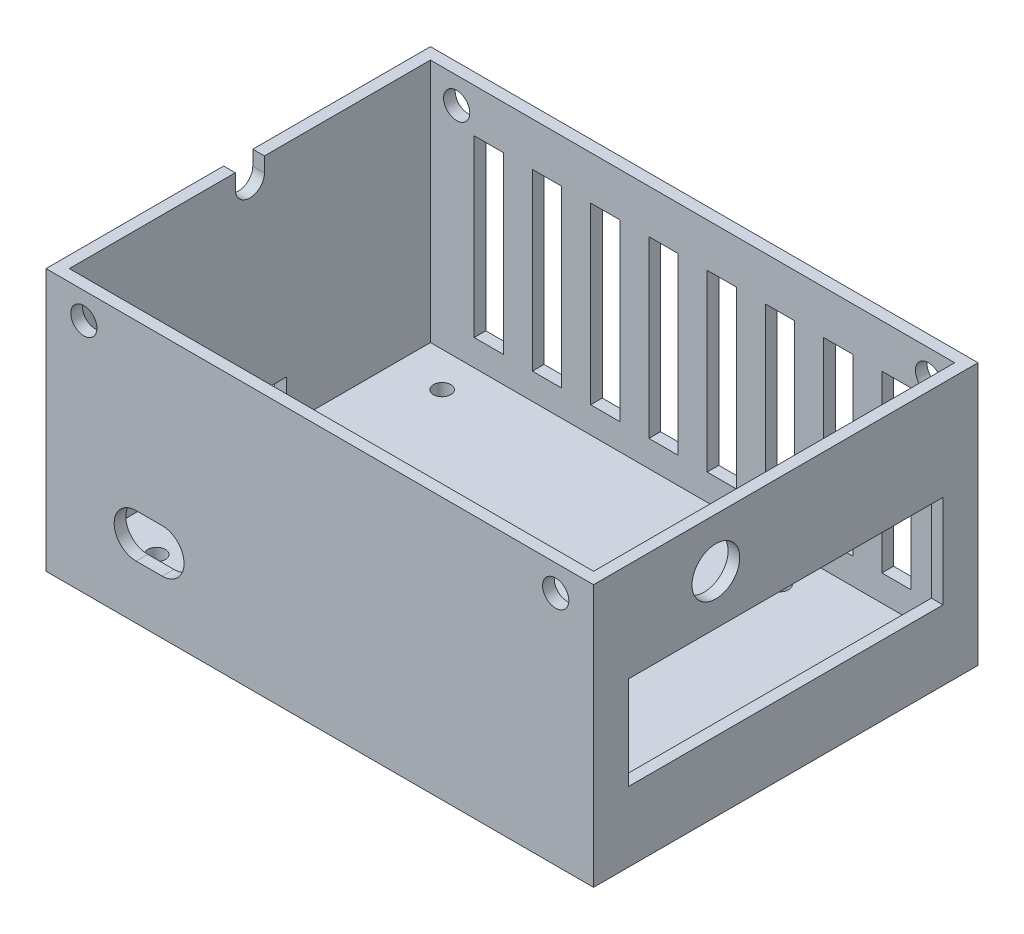
SolidWorks part; units mm, degrees
ref_plane "Front Plane" through (0, 0, 0) normal (0, 0, 1) x (1, 0, 0)
ref_plane "Top Plane" through (0, 0, 0) normal (0, 1, 0) x (1, 0, 0)
ref_plane "Right Plane" through (0, 0, 0) normal (1, 0, 0) x (0, 0, -1)
sketch "Sketch1" plane through (0, 0, 0) normal (0, 1, 0) x (1, 0, 0)
  line L1 (-45, -31) -> (45, -31)
  line L2 (-45, -31) -> (-45, 31)
  line L3 (-45, 31) -> (45, 31)
  line L4 (45, -31) -> (45, 31)
  line L5 (-45, -31) -> (45, 31) construction
  line L6 (-45, 31) -> (45, -31) construction
  point P0 (0, 0)
  dimension "D1" = 90
  dimension "D2" = 62
extrude "Boss-Extrude1" add sketch "Sketch1" along normal blind 3
sketch "Sketch2" plane through (0, 3, 0) normal (0, 1, 0) x (1, 0, 0)
  line L0 (-45, -31) -> (45, -31) construction
  line L1 (-45, 31) -> (-45, -31) construction
  circle A0 centre (-37, -24) radius 1.5
  circle A1 centre (21, -24) radius 1.5
  circle A2 centre (21, 25) radius 1.5
  circle A3 centre (-37, 25) radius 1.5
  dimension "D1" = 3
  dimension "D2" = 7
  dimension "D3" = 8
  dimension "D5" = 58
  dimension "D6" = 2
  dimension "D7" = 49
  dimension "D4" = 2
extrude "Cut-Extrude1" cut sketch "Sketch2" against normal up to next
sketch "Sketch3" plane through (0, 0, 0) normal (0, 1, 0) x (1, 0, 0)
  line L1 (-45, -31) -> (45, -31)
  line L2 (-45, -31) -> (-45, 31)
  line L3 (-45, 31) -> (45, 31)
  line L4 (45, -31) -> (45, 31)
  line L5 (-45, -31) -> (45, 31) construction
  line L6 (-45, 31) -> (45, -31) construction
  line L7 (-47, -33) -> (47, -33)
  line L8 (-47, -33) -> (-47, 33)
  line L9 (-47, 33) -> (47, 33)
  line L10 (47, -33) -> (47, 33)
  line L11 (-47, -33) -> (47, 33) construction
  line L12 (-47, 33) -> (47, -33) construction
  point P0 (0, 0)
  point P7 (0, 0)
  dimension "D1" = 2
  dimension "D2" = 2
extrude "Boss-Extrude2" add sketch "Sketch3" along normal blind 45
sketch "Sketch4" plane through (-45, 0, 0) normal (1, 0, 0) x (0, 0, -1)
  line L0 (0, 3) -> (0, 45) construction
  line L1 (31, 3) -> (-31, 3) construction
  line L2 (31, 45) -> (-31, 45) construction
  line L4 (-6.25, 10.25) -> (6.25, 10.25)
  line L5 (-6.25, 10.25) -> (-6.25, 7.75)
  line L6 (-6.25, 7.75) -> (6.25, 7.75)
  line L7 (6.25, 10.25) -> (6.25, 7.75)
  line L8 (-6.25, 10.25) -> (6.25, 7.75) construction
  line L9 (-6.25, 7.75) -> (6.25, 10.25) construction
  point P6 (0, 9)
  dimension "D1" = 6
  dimension "D2" = 2.5
  dimension "D3" = 12.5
extrude "Cut-Extrude2" cut sketch "Sketch4" against normal up to next
sketch "Sketch5" plane through (0, 0, 31) normal (0, 0, -1) x (-1, 0, 0)
  line L0 (29.3, 3) -> (29.3, 45) construction
  line L1 (45, 3) -> (-45, 3) construction
  line L2 (45, 45) -> (-45, 45) construction
  line L3 (45, 45) -> (45, 3) construction
  line L4 (31.55, 13) -> (27.05, 13) construction
  line L5 (31.55, 9.25) -> (27.05, 9.25)
  line L6 (31.55, 16.75) -> (27.05, 16.75)
  line L7 (35.3, 13) -> (23.3, 13) construction
  arc A0 (31.55, 9.25) -> (31.55, 16.75) centre (31.55, 13) ccw
  arc A1 (27.05, 16.75) -> (27.05, 9.25) centre (27.05, 13) ccw
  point P10 (29.3, 13)
  dimension "D4" = 10
  dimension "D1" = 15.7
  dimension "D2" = 7.5
  dimension "D3" = 12
extrude "Cut-Extrude3" cut sketch "Sketch5" against normal up to next
sketch "Sketch6" plane through (45, 0, 0) normal (-1, 0, 0) x (0, 0, 1)
  line L0 (0, 3) -> (0, 45) construction
  line L1 (31, 3) -> (-31, 3) construction
  line L2 (31, 45) -> (-31, 45) construction
  line L3 (31, 45) -> (31, 3) construction
  line L4 (-27, 12) -> (27, 12)
  line L5 (-27, 12) -> (-27, 28)
  line L6 (-27, 28) -> (27, 28)
  line L7 (27, 12) -> (27, 28)
  line L8 (-27, 12) -> (27, 28) construction
  line L9 (-27, 28) -> (27, 12) construction
  point P6 (0, 20)
  dimension "D1" = 9
  dimension "D2" = 16
  dimension "D3" = 4
extrude "Cut-Extrude4" cut sketch "Sketch6" against normal up to next
sketch "Sketch7" plane through (47, 0, 0) normal (1, 0, 0) x (0, 0, -1)
  line L0 (-27, 28) -> (-27, 45) construction
  line L1 (-33, 45) -> (33, 45) construction
  line L2 (-27, 36.5) -> (33, 36.5) construction
  line L3 (33, 45) -> (33, 0) construction
  circle A0 centre (-12, 36.5) radius 4.1
  dimension "D1" = 8.2
  dimension "D2" = 15
extrude "Cut-Extrude5" cut sketch "Sketch7" against normal up to next
sketch "Sketch8" plane through (0, 0, 33) normal (0, 0, 1) x (1, 0, 0)
  line L0 (-47, 45) -> (-47, 0) construction
  line L1 (-47, 45) -> (47, 45) construction
  line L2 (0, 45) -> (0, 0) construction
  line L3 (-47, 0) -> (47, 0) construction
  circle A0 centre (-40.5, 40.5) radius 2.25
  circle A1 centre (40.5, 40.5) radius 2.25
  dimension "D1" = 4.5
  dimension "D2" = 6.5
  dimension "D3" = 4.5
extrude "Cut-Extrude6" cut sketch "Sketch8" against normal through all
sketch "Sketch10" plane through (0, 0, -33) normal (0, 0, -1) x (-1, 0, 0)
  line L0 (0, 0) -> (0, 45) construction
  line L1 (-47, 45) -> (47, 45) construction
  line L2 (0, 22.5) -> (47, 22.5) construction
  line L3 (47, 45) -> (47, 0) construction
  line L4 (17.5, 37.5) -> (17.5, 7.5)
  line L5 (7.5, 37.5) -> (2.5, 37.5)
  line L6 (7.5, 37.5) -> (7.5, 7.5)
  line L7 (7.5, 7.5) -> (2.5, 7.5)
  line L8 (2.5, 37.5) -> (2.5, 7.5)
  line L9 (7.5, 37.5) -> (2.5, 7.5) construction
  line L10 (7.5, 7.5) -> (2.5, 37.5) construction
  line L11 (17.5, 37.5) -> (12.5, 37.5)
  line L12 (12.5, 37.5) -> (12.5, 7.5)
  line L13 (17.5, 7.5) -> (12.5, 7.5)
  line L14 (27.5, 37.5) -> (27.5, 7.5)
  line L15 (27.5, 37.5) -> (22.5, 37.5)
  line L16 (22.5, 37.5) -> (22.5, 7.5)
  line L17 (27.5, 7.5) -> (22.5, 7.5)
  line L18 (37.5, 37.5) -> (37.5, 7.5)
  line L19 (37.5, 37.5) -> (32.5, 37.5)
  line L20 (32.5, 37.5) -> (32.5, 7.5)
  line L21 (37.5, 7.5) -> (32.5, 7.5)
  line L30 (-7.5, 7.5) -> (-2.5, 7.5)
  line L31 (-2.5, 37.5) -> (-2.5, 7.5)
  line L32 (-7.5, 37.5) -> (-2.5, 37.5)
  line L33 (-7.5, 37.5) -> (-7.5, 7.5)
  line L34 (-17.5, 37.5) -> (-12.5, 37.5)
  line L35 (-12.5, 37.5) -> (-12.5, 7.5)
  line L36 (-17.5, 7.5) -> (-12.5, 7.5)
  line L37 (-17.5, 37.5) -> (-17.5, 7.5)
  line L38 (-27.5, 37.5) -> (-22.5, 37.5)
  line L39 (-22.5, 37.5) -> (-22.5, 7.5)
  line L40 (-27.5, 7.5) -> (-22.5, 7.5)
  line L41 (-27.5, 37.5) -> (-27.5, 7.5)
  line L42 (-37.5, 37.5) -> (-32.5, 37.5)
  line L43 (-32.5, 37.5) -> (-32.5, 7.5)
  line L44 (-37.5, 7.5) -> (-32.5, 7.5)
  line L45 (-37.5, 37.5) -> (-37.5, 7.5)
  line L54 (57.5, 37.5) -> (57.5, 7.5) [skipped]
  line L55 (57.5, 7.5) -> (52.5, 7.5) [skipped]
  line L56 (52.5, 37.5) -> (52.5, 7.5) [skipped]
  line L57 (57.5, 37.5) -> (52.5, 37.5) [skipped]
  line L58 (47.5, 37.5) -> (47.5, 7.5) [skipped]
  line L59 (47.5, 7.5) -> (42.5, 7.5) [skipped]
  line L60 (42.5, 37.5) -> (42.5, 7.5) [skipped]
  line L61 (47.5, 37.5) -> (42.5, 37.5) [skipped]
  point P9 (5, 22.5)
  dimension "D1" = 5
  dimension "D2" = 2.5
  dimension "D3" = 30
  dimension "D5" = 5
  dimension "D4" = 6
extrude "Cut-Extrude8" cut sketch "Sketch10" against normal up to next
sketch "Sketch11" plane through (-47, 0, 0) normal (-1, 0, 0) x (0, 0, 1)
  line L0 (0, 47.5) -> (0, 42.5) construction
  line L1 (-33, 45) -> (33, 45) construction
  line L2 (2.5, 47.5) -> (2.5, 42.5)
  line L3 (-2.5, 47.5) -> (-2.5, 42.5)
  arc A0 (2.5, 47.5) -> (-2.5, 47.5) centre (0, 47.5) ccw
  arc A1 (-2.5, 42.5) -> (2.5, 42.5) centre (0, 42.5) ccw
  point P5 (0, 45)
  dimension "D1" = 2.5
  dimension "D2" = 5
extrude "Cut-Extrude9" cut sketch "Sketch11" against normal up to next
sketch "Sketch12" plane through (0, 0, 0) normal (0, -1, 0) x (1, 0, 0)
  line L0 (-47, 0) -> (47, 0) construction
  line L1 (-47, -33) -> (-47, 33) construction
  line L2 (47, 33) -> (47, -33) construction
  circle A0 centre (-40, 0) radius 2.25
  circle A1 centre (-10, 0) radius 2.25
  dimension "D1" = 4.5
  dimension "D2" = 7
  dimension "D4" = 30
  dimension "D3" = 2
extrude "Cut-Extrude10" cut sketch "Sketch12" against normal up to next
